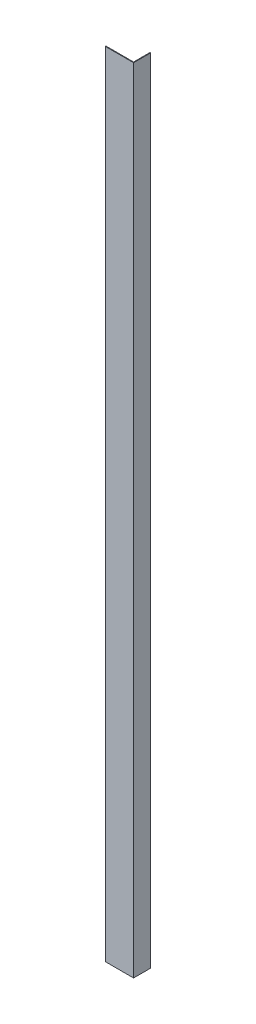
SolidWorks part; units mm, degrees
ref_plane "Front Plane" through (0, 0, 0) normal (0, 0, 1) x (1, 0, 0)
ref_plane "Top Plane" through (0, 0, 0) normal (0, 1, 0) x (1, 0, 0)
ref_plane "Right Plane" through (0, 0, 0) normal (1, 0, 0) x (0, 0, -1)
other "Configuration Table"
sketch "Sketch1" plane through (0, 0, 0) normal (0, 1, 0) x (1, 0, 0)
  line L0 (0, -40) -> (0, -38.5)
  line L1 (0, -38.5) -> (64.5, -38.5)
  line L2 (64.5, -38.5) -> (64.5, 0)
  line L3 (64.5, 0) -> (66, 0)
  line L4 (66, 0) -> (66, -40)
  line L5 (66, -40) -> (0, -40)
extrude "STORE_sove_sol_1" add sketch "Sketch1" along normal blind 1850 from offset 120 separate body
